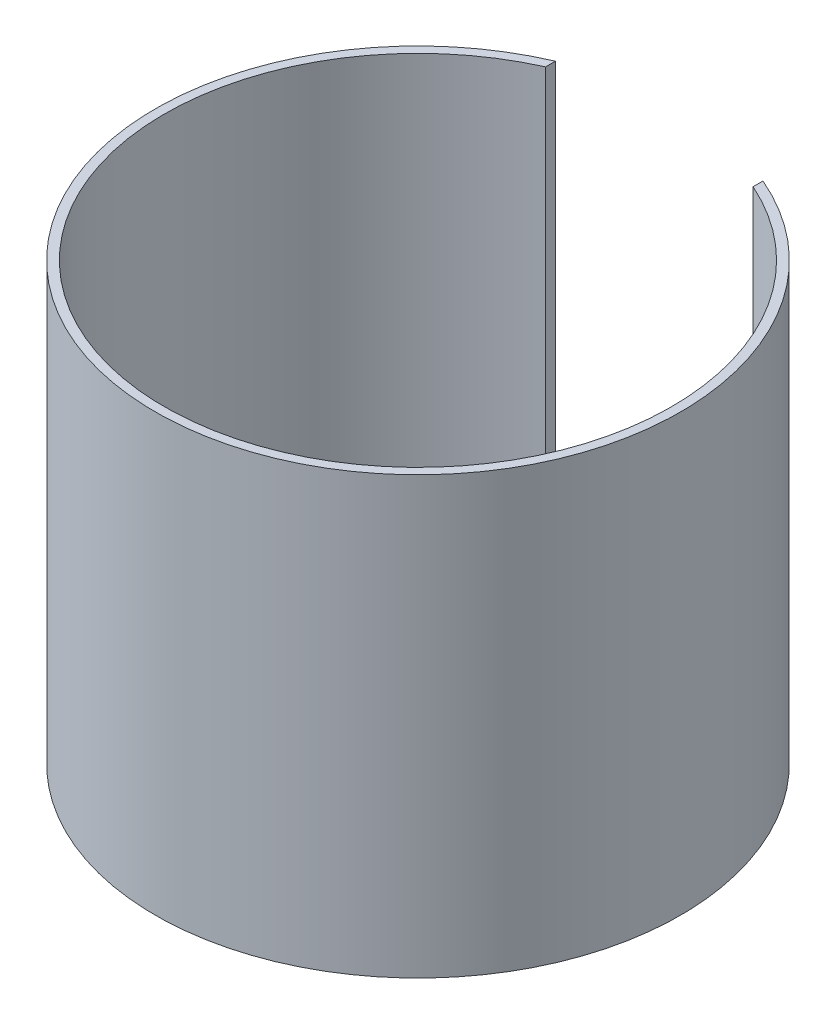
SolidWorks part; units mm, degrees
material "PTFE (general)"
ref_plane "Front Plane" through (0, 0, 0) normal (0, 0, 1) x (1, 0, 0)
ref_plane "Top Plane" through (0, 0, 0) normal (0, 1, 0) x (1, 0, 0)
ref_plane "Right Plane" through (0, 0, 0) normal (1, 0, 0) x (0, 0, -1)
sketch "Sketch1" plane through (0, 0, 0) normal (0, 1, 0) x (1, 0, 0)
  circle A0 centre (-43.2953, 2.0323) radius 28.506
  circle A1 centre (-43.2953, 2.0323) radius 29.522
  dimension "D1" = 57.012
extrude "Boss-Extrude1" add sketch "Sketch1" along normal blind 49
sketch "Sketch2" plane through (0, 0, 0) normal (0, 0, 1) x (1, 0, 0)
  line L0 (-72.8173, 0) -> (-13.7733, 0) construction
  line L1 (-54.9613, 19.5) -> (-54.9613, 49)
  line L2 (-14.7893, 49) -> (-71.8013, 49) construction
  line L3 (-54.9613, 49) -> (-31.6293, 49)
  line L4 (-31.6293, 49) -> (-31.6293, 19.5)
  line L5 (-54.9613, 19.5) -> (-54.9613, 0)
  line L6 (-54.9613, 0) -> (-31.6293, 0)
  line L7 (-31.6293, 0) -> (-31.6293, 19.5)
extrude "Cut-Extrude1" cut sketch "Sketch2" against normal blind 47
